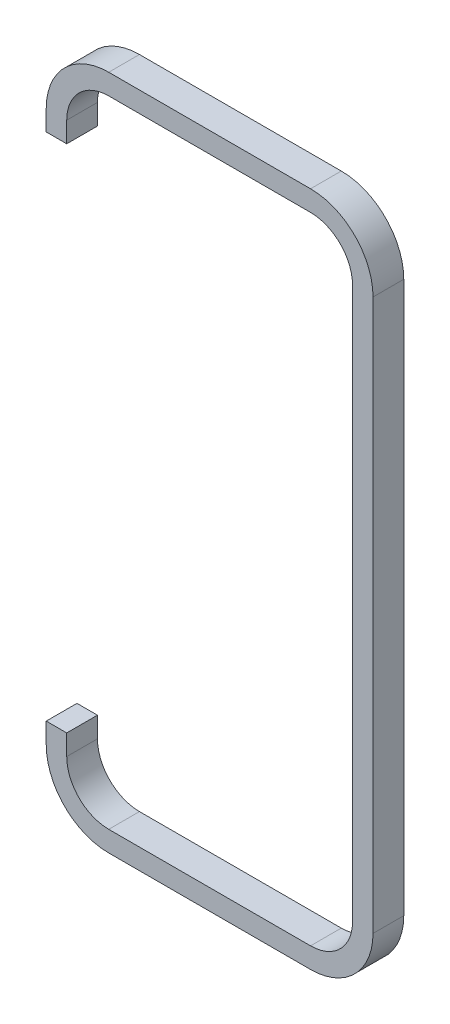
SolidWorks part; units mm, degrees
ref_plane "Front Plane" through (0, 0, 0) normal (1, 0, 0) x (0, 1, 0)
ref_plane "Top Plane" through (0, 0, 0) normal (0, 0, 1) x (0, 1, 0)
ref_plane "Right Plane" through (0, 0, 0) normal (0, 1, 0) x (-1, 0, 0)
sketch "Sketch1" plane through (0, 0, 0) normal (0, 0, 1) x (0, 1, 0)
  line L0 (-26.9, 13.95) -> (-24.9, 13.95)
  line L1 (-26.9, -13.85) -> (26.9, -13.85) construction
  line L2 (-30.9, -9.85) -> (-30.9, 9.85) construction
  line L3 (-26.9, 13.85) -> (26.9, 13.85) construction
  line L4 (30.9, -9.85) -> (30.9, 9.85) construction
  line L5 (-30.9, -13.85) -> (30.9, 13.85) construction
  line L6 (-30.9, 13.85) -> (30.9, -13.85) construction
  line L7 (31, -9.85) -> (31, 9.85)
  line L8 (-26.9, -13.95) -> (26.9, -13.95)
  line L9 (-31, -9.85) -> (-31, 9.85)
  line L10 (-26.9, 15.95) -> (-24.9, 15.95)
  line L11 (33, -9.85) -> (33, 9.85)
  line L12 (-26.9, -15.95) -> (26.9, -15.95)
  line L13 (-33, -9.85) -> (-33, 9.85)
  line L14 (-24.9, 15.95) -> (-24.9, 13.95)
  line L15 (0, 0) -> (0, 42.4171) construction
  line L16 (24.9, 15.95) -> (24.9, 13.95)
  line L17 (24.9, 15.95) -> (26.9, 15.95)
  line L18 (-26.9, 15.95) -> (26.9, 15.95) construction
  line L19 (24.9, 13.95) -> (26.9, 13.95)
  line L20 (-26.9, 13.95) -> (26.9, 13.95) construction
  arc A0 (-30.9, 9.85) -> (-26.9, 13.85) centre (-26.9, 9.85) cw construction
  arc A1 (-26.9, -13.85) -> (-30.9, -9.85) centre (-26.9, -9.85) cw construction
  arc A2 (26.9, -13.85) -> (30.9, -9.85) centre (26.9, -9.85) ccw construction
  arc A3 (26.9, 13.85) -> (30.9, 9.85) centre (26.9, 9.85) cw construction
  arc A4 (26.9, 13.95) -> (31, 9.85) centre (26.9, 9.85) cw
  arc A5 (26.9, -13.95) -> (31, -9.85) centre (26.9, -9.85) ccw
  arc A6 (-26.9, -13.95) -> (-31, -9.85) centre (-26.9, -9.85) cw
  arc A7 (-31, 9.85) -> (-26.9, 13.95) centre (-26.9, 9.85) cw
  arc A8 (26.9, 15.95) -> (33, 9.85) centre (26.9, 9.85) cw
  arc A9 (26.9, -15.95) -> (33, -9.85) centre (26.9, -9.85) ccw
  arc A10 (-26.9, -15.95) -> (-33, -9.85) centre (-26.9, -9.85) cw
  arc A11 (-33, 9.85) -> (-26.9, 15.95) centre (-26.9, 9.85) cw
  point P0 (0, 0)
  dimension "D3" = 4
  dimension "D1" = 61.8
  dimension "D2" = 27.7
  dimension "D6" = 2
  dimension "D4" = 0.1
  dimension "D5" = 2
extrude "Boss-Extrude1" add sketch "Sketch1" along normal blind 3
